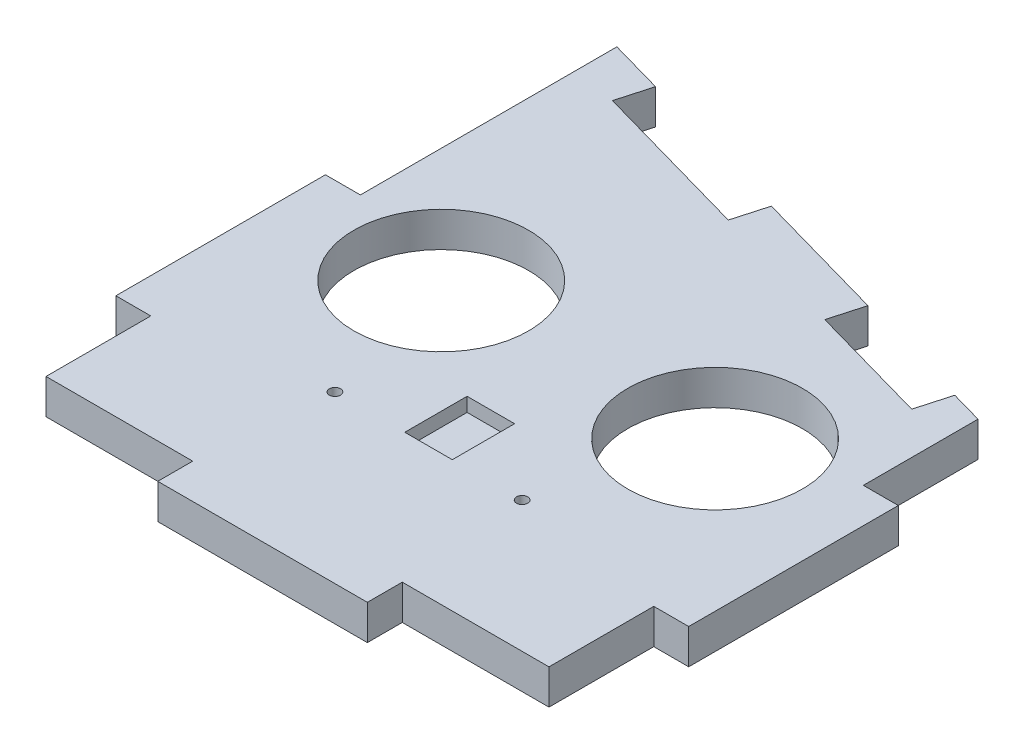
SolidWorks part; units mm, degrees
ref_plane "Front Plane" through (0, 0, 0) normal (0, 0, 1) x (1, 0, 0)
ref_plane "Top Plane" through (0, 0, 0) normal (0, 1, 0) x (1, 0, 0)
ref_plane "Right Plane" through (0, 0, 0) normal (1, 0, 0) x (0, 0, -1)
sketch "Sketch1" plane through (0, 0, 0) normal (0, 1, 0) x (1, 0, 0)
  line L0 (16.51, 0) -> (3.175, 0)
  line L1 (16.51, 0) -> (16.51, -3.175)
  line L2 (16.51, -3.175) -> (35.56, -3.175)
  line L3 (35.56, -3.175) -> (35.56, 0)
  line L4 (35.56, 0) -> (48.895, 0)
  line L5 (48.895, 0) -> (48.895, 9.525)
  line L6 (52.07, 9.525) -> (48.895, 9.525)
  line L7 (45.9585, 39.824) -> (48.895, 38.9956)
  line L8 (48.895, 28.575) -> (52.07, 28.575)
  line L9 (48.895, 38.9956) -> (52.07, 38.1) construction
  line L10 (52.07, 28.575) -> (52.07, 9.525)
  line L11 (8.0672, 50.5125) -> (3.175, 51.8925)
  line L12 (0, 28.575) -> (3.175, 28.575)
  line L13 (0, 28.575) -> (0, 9.525)
  line L14 (3.175, 9.525) -> (0, 9.525)
  line L16 (52.07, 38.1) -> (31.283, 38.1) construction
  line L17 (13.589, 25.5124) -> (38.481, 25.5124) construction
  line L18 (26.035, 25.5124) -> (26.035, -3.175) construction
  line L19 (45.9585, 39.824) -> (45.0965, 36.7682)
  line L20 (45.0965, 36.7682) -> (34.0958, 39.8713)
  line L21 (34.0958, 39.8713) -> (34.9578, 42.9271)
  line L22 (34.9578, 42.9271) -> (22.7348, 46.375)
  line L23 (22.7348, 46.375) -> (21.8728, 43.3193)
  line L24 (21.8728, 43.3193) -> (7.2052, 47.4568)
  line L25 (7.2052, 47.4568) -> (8.0672, 50.5125)
  line L27 (3.175, 28.575) -> (3.175, 51.8925)
  line L28 (3.175, 9.525) -> (3.175, 0)
  line L29 (48.895, 28.575) -> (48.895, 38.9956)
  line L30 (48.895, 9.525) -> (48.895, 0) construction
  circle A0 centre (13.589, 25.5124) radius 7.9375
  circle A1 centre (38.481, 25.5124) radius 7.9375
  dimension "D1" = 15.875
  dimension "D2" = 19.05
  dimension "D3" = 3.175
  dimension "D5" = 3.175
  dimension "D6" = 19.05
  dimension "D7" = 19.05
  dimension "D8" = 24.892
  dimension "D9" = 15.24
  dimension "D10" = 11.43
  dimension "D12" = 12.7
  dimension "D15" = 51.8925
  dimension "D16" = 38.9956
extrude "Boss-Extrude1" add sketch "Sketch1" along normal blind 3.175
sketch "Sketch2" plane through (0, 3.175, 0) normal (0, 1, 0) x (1, 0, 0)
  line L0 (38.481, 17.5749) -> (20.6827, 17.5749) construction
  line L1 (23.876, 17.5749) -> (28.194, 17.5749)
  line L2 (23.876, 17.5749) -> (23.876, 11.9107)
  line L3 (23.876, 11.9107) -> (28.194, 11.9107)
  line L4 (28.194, 17.5749) -> (28.194, 11.9107)
  line L5 (26.035, -3.175) -> (26.035, 11.9107) construction
  line L6 (16.51, -3.175) -> (35.56, -3.175) construction
  circle A0 centre (38.481, 25.5124) radius 7.9375 construction
  dimension "D1" = 5.6642
  dimension "D2" = 4.318
extrude "Cut-Extrude1" cut sketch "Sketch2" against normal blind 1.27
sketch "Sketch3" plane through (0, 3.175, 0) normal (0, 1, 0) x (1, 0, 0)
  line L0 (23.876, 11.9107) -> (17.526, 11.9107) construction
  line L1 (28.194, 11.9107) -> (34.544, 11.9107) construction
  circle A0 centre (17.526, 11.9107) radius 0.508
  circle A1 centre (34.544, 11.9107) radius 0.508
  dimension "D1" = 1.016
  dimension "D2" = 6.35
extrude "Cut-Extrude2" cut sketch "Sketch3" against normal through all
